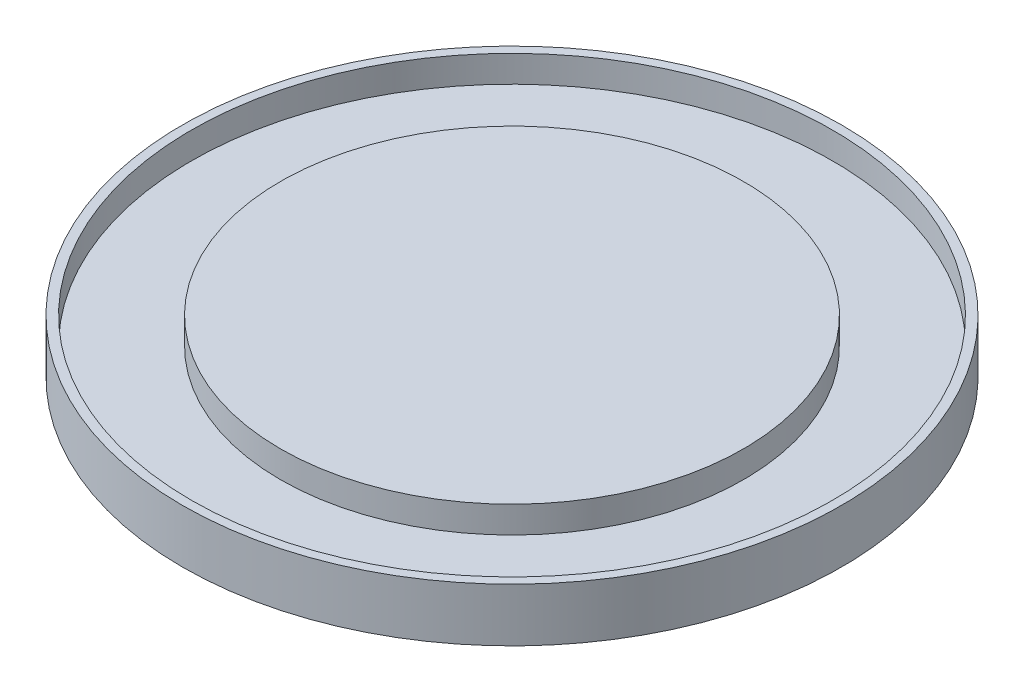
SolidWorks part; units mm, degrees
ref_plane "Front Plane" through (0, 0, 0) normal (0, 0, 1) x (1, 0, 0)
ref_plane "Top Plane" through (0, 0, 0) normal (0, 1, 0) x (1, 0, 0)
ref_plane "Right Plane" through (0, 0, 0) normal (1, 0, 0) x (0, 0, -1)
sketch "Sketch1" plane through (0, 0, 0) normal (0, 1, 0) x (1, 0, 0)
  circle A0 centre (0, 0) radius 18.5
  dimension "D1" = 37
extrude "Boss-Extrude1" add sketch "Sketch1" along normal blind 3
sketch "Sketch2" plane through (0, 3, 0) normal (0, 1, 0) x (1, 0, 0)
  circle A0 centre (0, 0) radius 13
  circle A1 centre (0, 0) radius 18
  dimension "D1" = 26
  dimension "D2" = 36
extrude "Cut-Extrude1" cut sketch "Sketch2" against normal blind 1.5
scale "Scale1" bodies to scale 102 scale about centroid uniform scaling yes scale factor 0.8
